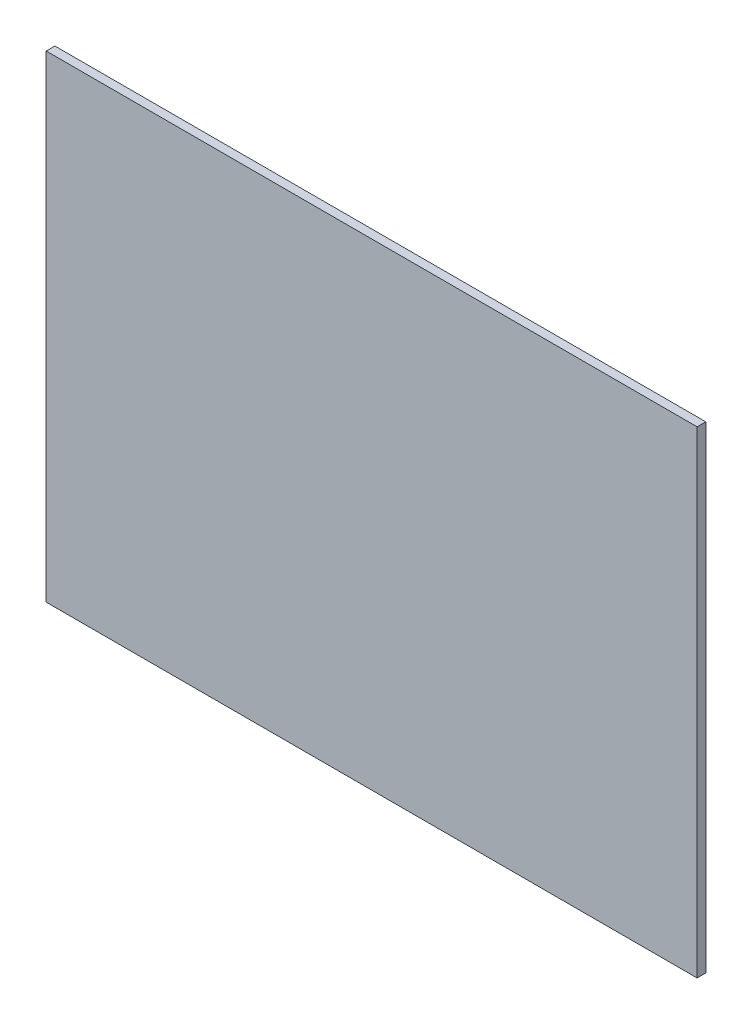
SolidWorks part; units mm, degrees
ref_plane "Alzado" through (0, 0, 0) normal (0, 0, 1) x (1, 0, 0)
ref_plane "Planta" through (0, 0, 0) normal (0, 1, 0) x (1, 0, 0)
ref_plane "Vista lateral" through (0, 0, 0) normal (1, 0, 0) x (0, 0, -1)
sketch "Croquis1" plane through (0, 0, 0) normal (0, 0, 1) x (1, 0, 0)
  line L1 (0, 0) -> (300, 0)
  line L2 (0, 0) -> (0, 220)
  line L3 (0, 220) -> (300, 220)
  line L4 (300, 0) -> (300, 220)
  dimension "D1" = 220
  dimension "D2" = 300
extrude "Saliente-Extruir1" add sketch "Croquis1" along normal blind 4
